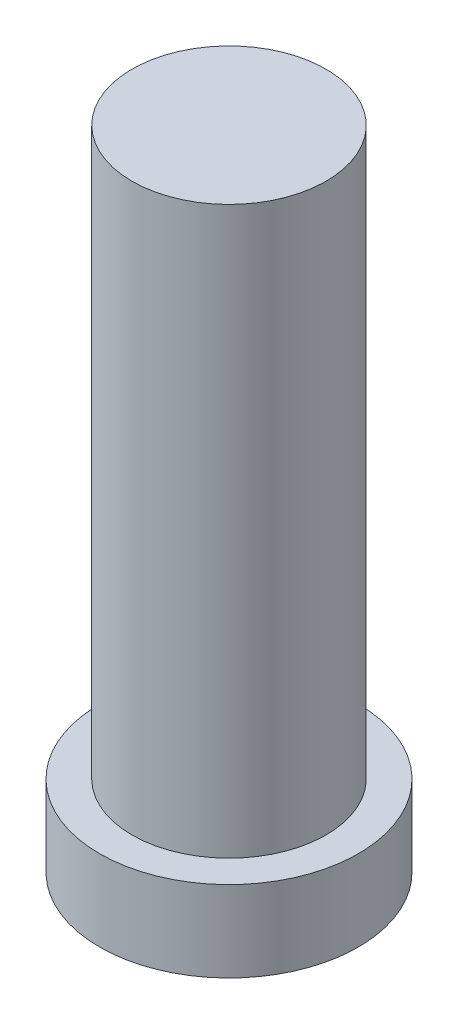
SolidWorks part; units mm, degrees
ref_plane "前视基准面" through (0, 0, 0) normal (0, 0, 1) x (1, 0, 0)
ref_plane "上视基准面" through (0, 0, 0) normal (0, 1, 0) x (1, 0, 0)
ref_plane "右视基准面" through (0, 0, 0) normal (1, 0, 0) x (0, 0, -1)
other "Configuration Table"
sketch "草图1" plane through (0, 0, 0) normal (0, 1, 0) x (1, 0, 0)
  circle A0 centre (0, 0) radius 80
  point P3 (0, 0)
  point P4 (0, 0)
  dimension "D1" = 160
extrude "凸台-拉伸1" add sketch "草图1" against normal blind 50
sketch "草图2" plane through (0, 0, 0) normal (0, 1, 0) x (1, 0, 0)
  circle A0 centre (0, 0) radius 60
  dimension "D1" = 120
extrude "凸台-拉伸2" add sketch "草图2" along normal blind 350
